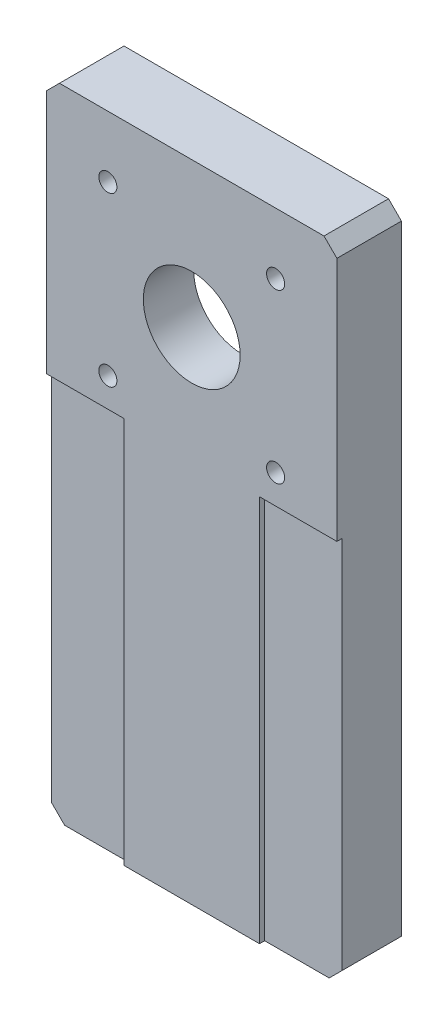
SolidWorks part; units mm, degrees
ref_plane "Front Plane" through (0, 0, 0) normal (0, 0, 1) x (1, 0, 0)
ref_plane "Top Plane" through (0, 0, 0) normal (0, 1, 0) x (1, 0, 0)
ref_plane "Right Plane" through (0, 0, 0) normal (1, 0, 0) x (0, 0, -1)
sketch "Sketch1" plane through (0, 0, 0) normal (0, 0, 1) x (1, 0, 0)
  line L1 (0, 0) -> (45, 0)
  line L2 (0, 0) -> (0, 100)
  line L3 (0, 100) -> (45, 100)
  line L4 (45, 0) -> (45, 100)
  dimension "D1" = 45
  dimension "D2" = 100
extrude "Boss-Extrude1" add sketch "Sketch1" along normal blind 10
sketch "Sketch3" plane through (0, 0, 10) normal (0, 0, 1) x (1, 0, 0)
  line L0 (45, 0) -> (45, 100) construction
  line L1 (45, 100) -> (0, 100) construction
  circle A0 centre (22.5, 77.5) radius 7.5
  circle A1 centre (9.5, 90.5) radius 1.4
  circle A2 centre (35.5, 90.5) radius 1.4
  circle A3 centre (35.5, 64.5) radius 1.4
  circle A4 centre (9.5, 64.5) radius 1.4
  dimension "D1" = 15
  dimension "D2" = 22.5
  dimension "D3" = 22.5
  dimension "D4" = 2.8
  dimension "D5" = 2.8
  dimension "D6" = 2.8
  dimension "D7" = 2.8
  dimension "D8" = 13
  dimension "D9" = 13
  dimension "D10" = 13
  dimension "D11" = 13
  dimension "D12" = 13
  dimension "D13" = 13
  dimension "D14" = 13
  dimension "D15" = 13
extrude "Cut-Extrude1" cut sketch "Sketch3" against normal blind 10
sketch "Sketch4" plane through (0, 0, 0) normal (0, 0, -1) x (-1, 0, 0)
  circle A0 centre (-22.5, 77.5) radius 11
  dimension "D1" = 22
extrude "Cut-Extrude2" cut sketch "Sketch4" against normal blind 2.2
sketch "Sketch5" plane through (0, 0, 0) normal (0, -1, 0) x (1, 0, 0)
  line L1 (0, 10) -> (12, 10)
  line L2 (0, 10) -> (0, 9.2)
  line L3 (0, 9.2) -> (12, 9.2)
  line L4 (12, 10) -> (12, 9.2)
  line L5 (45, 10) -> (33, 10)
  line L6 (45, 10) -> (45, 9.2)
  line L7 (45, 9.2) -> (33, 9.2)
  line L8 (33, 10) -> (33, 9.2)
  dimension "D1" = 12
  dimension "D2" = 12
  dimension "D3" = 0.8
  dimension "D4" = 0.8
extrude "Cut-Extrude3" cut sketch "Sketch5" against normal blind 60
chamfer "Chamfer1" distance 2 angle 45 4 edges at (0, 0, 4.6) (45, 0, 4.6) (45, 100, 5) (0, 100, 5)
